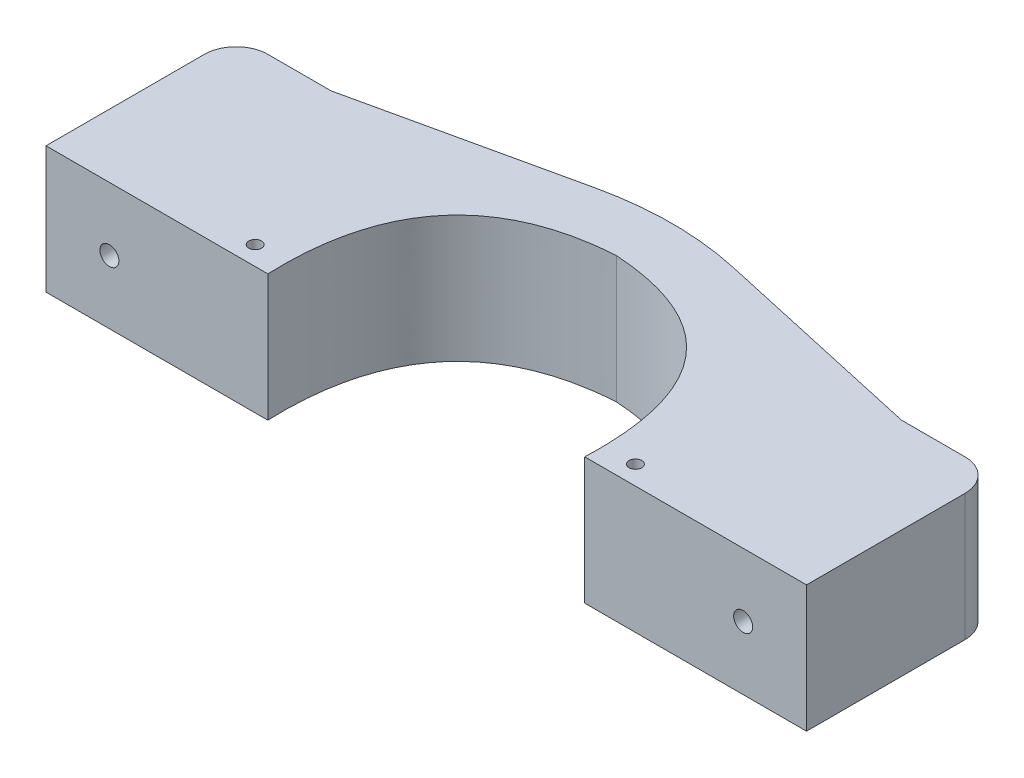
SolidWorks part; units mm, degrees
ref_plane "Front Plane" through (0, 0, 0) normal (0, 0, 1) x (1, 0, 0)
ref_plane "Top Plane" through (0, 0, 0) normal (0, 1, 0) x (1, 0, 0)
ref_plane "Right Plane" through (0, 0, 0) normal (1, 0, 0) x (0, 0, -1)
sketch "Sketch2" plane through (0, 0, 0) normal (0, 1, 0) x (1, 0, 0)
  line L0 (25, -30) -> (60, -30)
  line L1 (60, -30) -> (60, 0)
  line L2 (0, 10) -> (45, 0)
  line L3 (0, 10) -> (0, -49.7951) construction
  line L4 (-45, 0) -> (-60, 0)
  line L5 (0, 10) -> (-45, 0)
  line L6 (-60, -30) -> (-60, 0)
  line L7 (45, 0) -> (60, 0)
  line L8 (-25, -30) -> (-60, -30)
  spline S0 degree 2 poles (0, 0) (26.0776, -1.6586) (25, -30) knots 0 0 0 1 1 1
  spline S1 degree 2 poles (0, 0) (-26.0776, -1.6586) (-25, -30) knots 0 0 0 1 1 1
  dimension "D1" = 60
  dimension "D2" = 25
  dimension "D3" = 10
  dimension "D4" = 30
  dimension "D5" = 30
  dimension "D6" = 24
  dimension "D7" = 17
  dimension "D8" = 15
extrude "Boss-Extrude1" add sketch "Sketch2" along normal blind 20
fillet "Fillet1" radius 50 1 edges at (0, 10, -10)
fillet "Fillet2" radius 5 2 edges at (60, 10, 0) (-60, 10, 0)
sketch "Sketch3" plane through (0, 0, 30) normal (0, 0, 1) x (1, 0, 0)
  line L0 (60, 20) -> (60, 0) construction
  circle A0 centre (50, 10) radius 1.5
  point P0 (0, 0)
  point P6 (49.0957, 10)
  dimension "D2" = 3
  dimension "D1" = 10
extrude "Cut-Extrude1" cut sketch "Sketch3" against normal blind 20
sketch "Sketch4" plane through (0, 0, 0) normal (0, 0, -1) x (-1, 0, 0)
  circle A0 centre (-50, 10) radius 2.5
  dimension "D1" = 5
extrude "Cut-Extrude2" cut sketch "Sketch4" against normal blind 10
mirror "Mirror1" about plane through (0, 0, 0) normal (1, 0, 0) of "Cut-Extrude2", "Cut-Extrude1"
sketch "Sketch5" plane through (0, 20, 0) normal (0, 1, 0) x (1, 0, 0)
  line L0 (25, -30) -> (60, -30) construction
  circle A0 centre (30, -27) radius 1
  dimension "D1" = 3
  dimension "D2" = 2
  dimension "D3" = 5
extrude "Cut-Extrude3" cut sketch "Sketch5" against normal up to surface (20 mm away) up to face at (-1.9231, 0, 8.5815)
mirror "Mirror2" about plane through (0, 0, 0) normal (1, 0, 0) of "Cut-Extrude3"
ref_plane "Plane1" through (0, 0, 0) normal (1, 0, 0) x (0, 0, -1)
